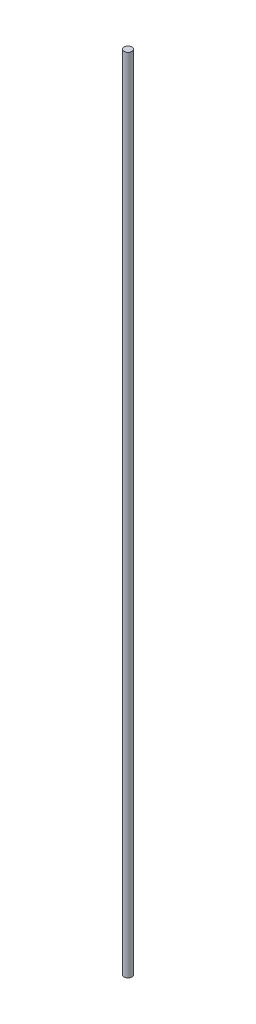
SolidWorks part; units mm, degrees
ref_plane "Front Plane" through (0, 0, 0) normal (0, 0, 1) x (1, 0, 0)
ref_plane "Top Plane" through (0, 0, 0) normal (0, 1, 0) x (1, 0, 0)
ref_plane "Right Plane" through (0, 0, 0) normal (1, 0, 0) x (0, 0, -1)
sketch "Sketch1" plane through (0, 0, 0) normal (0, 1, 0) x (1, 0, 0)
  circle A0 centre (0, 0) radius 4
extrude "Boss-Extrude1" add sketch "Sketch1" along normal blind 822.96
